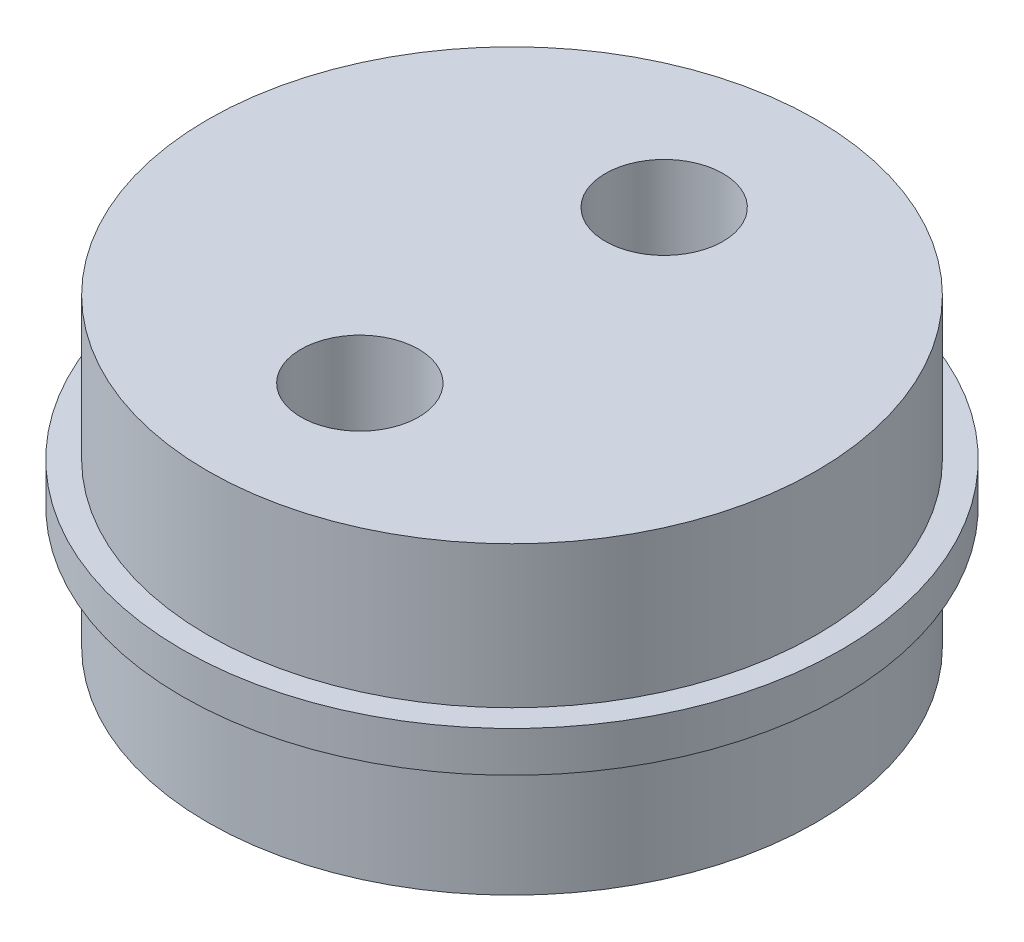
SolidWorks part; units mm, degrees
ref_plane "Front Plane" through (0, 0, 0) normal (0, 0, 1) x (1, 0, 0)
ref_plane "Top Plane" through (0, 0, 0) normal (0, 1, 0) x (1, 0, 0)
ref_plane "Right Plane" through (0, 0, 0) normal (1, 0, 0) x (0, 0, -1)
sketch "Sketch1" plane through (0, 0, 0) normal (0, 1, 0) x (1, 0, 0)
  circle A0 centre (0, 0) radius 16.25
  dimension "D1" = 32.5
extrude "Boss-Extrude1" add sketch "Sketch1" along normal blind 2
sketch "Sketch2" plane through (0, 0, 0) normal (0, -1, 0) x (1, 0, 0)
  circle A0 centre (0, 0) radius 15
  circle A1 centre (0, 0) radius 15 construction
extrude "Boss-Extrude2" add sketch "Sketch2" along normal blind 6
sketch "Sketch3" plane through (0, 2, 0) normal (0, 1, 0) x (1, 0, 0)
  circle A0 centre (0, 0) radius 15
  dimension "D1" = 30
extrude "Boss-Extrude3" add sketch "Sketch3" along normal blind 7
sketch "Sketch4" plane through (0, 9, 0) normal (0, 1, 0) x (1, 0, 0)
  line L1 (-4.4, 0) -> (4.4, 0) construction
  circle A0 centre (0, 7.5) radius 2.9
  circle A2 centre (0, -7.5) radius 2.9
  dimension "D1" = 5.8
  dimension "D2" = 7.5
extrude "Cut-Extrude1" cut sketch "Sketch4" against normal blind 8 and the other way through all
sketch "Sketch5" plane through (0, 1, 0) normal (0, 1, 0) x (1, 0, 0)
  circle A0 centre (0, 7.5) radius 2.2
  circle A1 centre (0, -7.5) radius 2.2
  dimension "D1" = 4.4
extrude "Cut-Extrude2" cut sketch "Sketch5" against normal through all both and the other way through all
